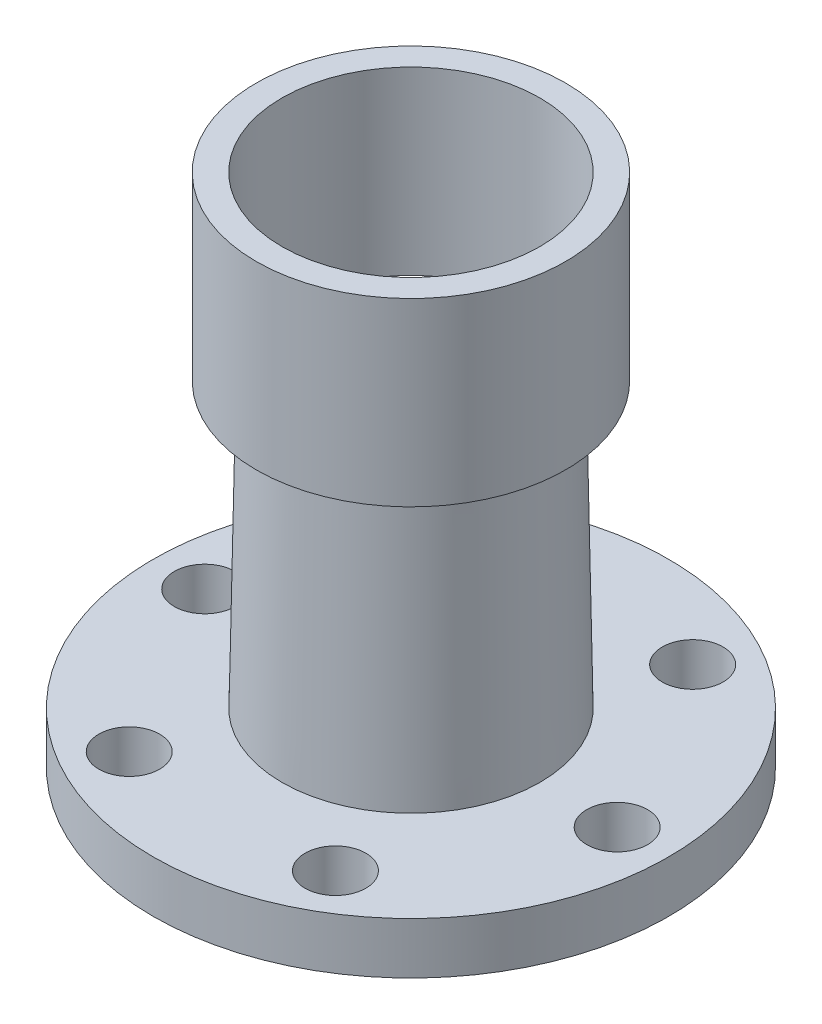
SolidWorks part; units mm, degrees
ref_plane "Front Plane" through (0, 0, 0) normal (0, 0, 1) x (1, 0, 0)
ref_plane "Top Plane" through (0, 0, 0) normal (0, 1, 0) x (1, 0, 0)
ref_plane "Right Plane" through (0, 0, 0) normal (1, 0, 0) x (0, 0, -1)
sketch "Sketch1" plane through (0, 0, 0) normal (0, 1, 0) x (1, 0, 0)
  circle A0 centre (0, 0) radius 50
  dimension "D1" = 100
extrude "Boss-Extrude1" add sketch "Sketch1" along normal mid plane 10
sketch "Sketch2" plane through (0, 5, 0) normal (0, 1, 0) x (1, 0, 0)
  circle A0 centre (0, 0) radius 20
  circle A2 centre (0, 0) radius 25
  dimension "D1" = 40
  dimension "D2" = 50
extrude "Boss-Extrude2" add sketch "Sketch2" along normal blind 55 draft 1
sketch "Sketch3" plane through (0, 60, 0) normal (0, 1, 0) x (1, 0, 0)
  circle A0 centre (0, 0) radius 30
  circle A1 centre (0, 0) radius 25
  dimension "D1" = 60
  dimension "D2" = 50
extrude "Boss-Extrude3" add sketch "Sketch3" along normal blind 35 separate body
hole_wizard "Hole1" positions "Sketch4" profile "Sketch5" legacy end condition up to next
sketch "Sketch4" plane through (0, 5, 0) normal (0, 1, 0) x (1, 0, 0)
  point P0 (40, 0)
  point P4 (0, 0)
  dimension "D1" = 40
sketch "Sketch5" plane through (40, 5, 0) normal (1, 0, 0) x (0, 0, 1)
  line L0 (0, 0) -> (0, 10)
  line L1 (0, 10) -> (5.9, 10)
  line L2 (5.9, 10) -> (5.9, 0)
  line L3 (5.9, 0) -> (0, 0)
  line L4 (0, 110) -> (0, -10) construction
  dimension "Diameter" = 11.8
  dimension "Depth" = 10
pattern_circular "CirPattern1" count 6 over 360 about axis through (0, 0, 0) along (0, 1, 0) of "Hole1"
